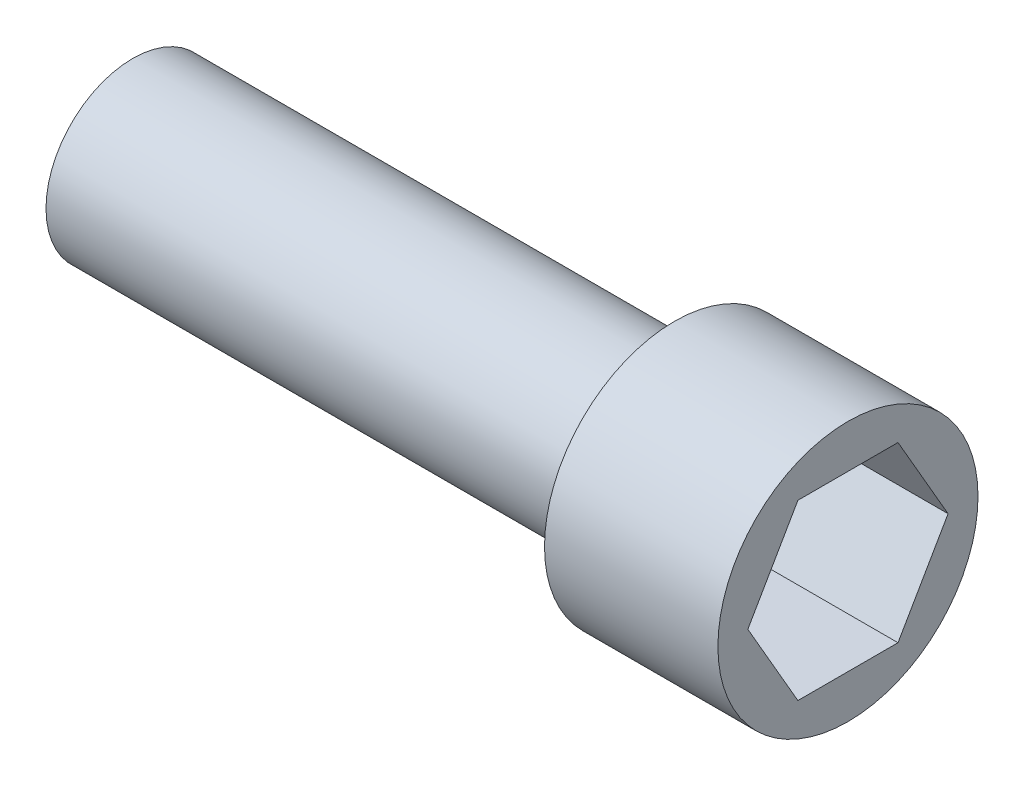
SolidWorks part; units mm, degrees
material "AISI 1010 Steel, hot rolled bar"
ref_plane "Front Plane" through (0, 0, 0) normal (0, 0, 1) x (1, 0, 0)
ref_plane "Top Plane" through (0, 0, 0) normal (0, 1, 0) x (1, 0, 0)
ref_plane "Right Plane" through (0, 0, 0) normal (1, 0, 0) x (0, 0, -1)
sketch "Sketch1" plane through (0, 0, 0) normal (0, 0, 1) x (1, 0, 0)
  line L0 (0, 0) -> (0, 4)
  line L1 (0, 4) -> (25, 4)
  line L2 (25, 4) -> (25, 6)
  line L3 (25, 6) -> (33, 6)
  line L4 (33, 6) -> (33, 0)
  line L5 (33, 0) -> (0, 0)
  dimension "D1" = 33
  dimension "D2" = 4
  dimension "D3" = 25
  dimension "D4" = 6
revolve "Revolve1" add sketch "Sketch1" angle 360 about L5
sketch "Sketch2" plane through (33, 0, 0) normal (1, 0, 0) x (0, 0, -1)
  line L1 (4.6188, 0) -> (2.3094, 4)
  line L2 (2.3094, 4) -> (-2.3094, 4)
  line L3 (-2.3094, 4) -> (-4.6188, 0)
  line L4 (-4.6188, 0) -> (-2.3094, -4)
  line L5 (-2.3094, -4) -> (2.3094, -4)
  line L6 (2.3094, -4) -> (4.6188, 0)
  circle A0 centre (0, 0) radius 4 construction
  dimension "D1" = 8
extrude "Cut-Extrude1" cut sketch "Sketch2" against normal blind 6
